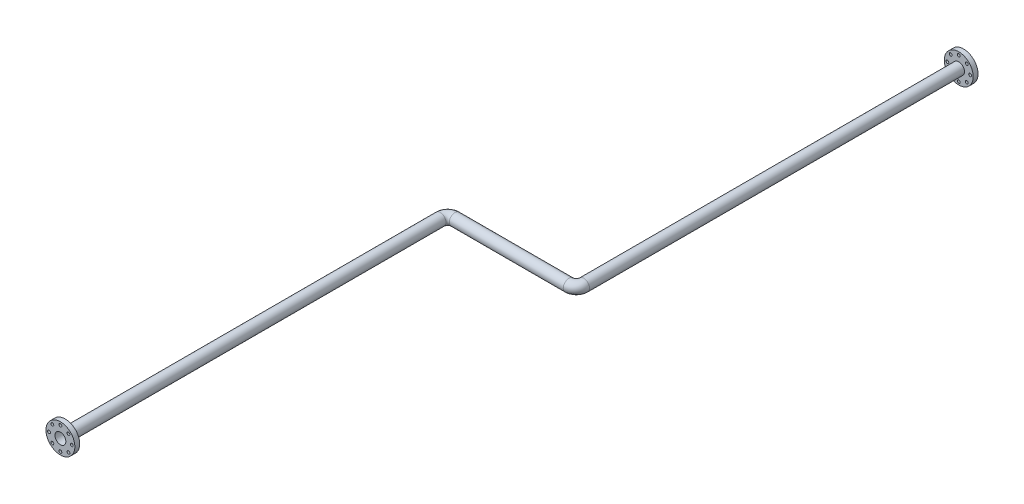
SolidWorks part; units mm, degrees
ref_plane "정면" through (0, 0, 0) normal (0, 0, 1) x (1, 0, 0)
ref_plane "윗면" through (0, 0, 0) normal (0, 1, 0) x (1, 0, 0)
ref_plane "우측면" through (0, 0, 0) normal (1, 0, 0) x (0, 0, -1)
sketch "스케치1" plane through (0, 0, 0) normal (1, 0, 0) x (0, 0, -1)
  circle A0 centre (0, 0) radius 30.25
  circle A1 centre (0, 0) radius 28.65
  dimension "D1" = 60.5
  dimension "D2" = 57.3
extrude "보스-돌출1" add sketch "스케치1" along normal mid plane 600
sketch "스케치2" plane through (300, 0, 0) normal (1, 0, 0) x (0, 0, -1)
  line L0 (39, 37.7289) -> (39, -37.7289) construction
  circle A0 centre (0, 0) radius 28.65
  circle A1 centre (0, 0) radius 30.25
  circle A2 centre (0, 0) radius 30.25 construction
  circle A3 centre (0, 0) radius 28.65 construction
  point P7 (39, 0)
  dimension "D1" = 39
revolve "회전1" add sketch "스케치2" angle 90 about L0
sketch "스케치3" plane through (-300, 0, 0) normal (-1, 0, 0) x (0, 0, 1)
  line L0 (39, 42.1657) -> (39, -42.1657) construction
  circle A0 centre (0, 0) radius 28.65
  circle A1 centre (0, 0) radius 30.25
  circle A2 centre (0, 0) radius 30.25 construction
  circle A3 centre (0, 0) radius 28.65 construction
  point P6 (39, 0)
  dimension "D1" = 39
revolve "회전2" add sketch "스케치3" angle 90 about L0
sketch "스케치4" plane through (0, 0, -39) normal (0, 0, -1) x (-1, 0, 0)
  circle A0 centre (-339, 0) radius 28.65
  circle A1 centre (-339, 0) radius 30.25
  circle A2 centre (-339, 0) radius 30.25 construction
  circle A3 centre (-339, 0) radius 28.65 construction
extrude "보스-돌출2" add sketch "스케치4" along normal blind 2000
sketch "스케치5" plane through (0, 0, 39) normal (0, 0, 1) x (1, 0, 0)
  circle A0 centre (-339, 0) radius 28.65
  circle A1 centre (-339, 0) radius 30.25
  circle A2 centre (-339, 0) radius 30.25 construction
  circle A3 centre (-339, 0) radius 28.65 construction
extrude "보스-돌출3" add sketch "스케치5" along normal blind 2000
sketch "스케치6" plane through (0, 0, 2039) normal (0, 0, 1) x (1, 0, 0)
  line L0 (-339, 60) -> (-339, 0) construction
  circle A0 centre (-339, 0) radius 76
  circle A1 centre (-339, 0) radius 28.65
  circle A2 centre (-339, 0) radius 28.65 construction
  circle A3 centre (-339, 60) radius 7.5
  circle A4 centre (-296.5736, 42.4264) radius 7.5
  circle A5 centre (-279, 0) radius 7.5
  circle A6 centre (-296.5736, -42.4264) radius 7.5
  circle A7 centre (-339, -60) radius 7.5
  circle A8 centre (-381.4264, -42.4264) radius 7.5
  circle A9 centre (-399, 0) radius 7.5
  circle A10 centre (-381.4264, 42.4264) radius 7.5
  point P24 (-339, 0)
  dimension "D1" = 152
  dimension "D2" = 15
  dimension "D3" = 60
  dimension "D4" = 8
extrude "보스-돌출4" add sketch "스케치6" against normal blind 25.5
sketch "스케치7" plane through (0, 0, -2039) normal (0, 0, -1) x (-1, 0, 0)
  line L0 (-339, 0) -> (-339, 60) construction
  circle A0 centre (-339, 0) radius 76
  circle A1 centre (-339, 0) radius 28.65
  circle A2 centre (-339, 0) radius 28.65 construction
  circle A3 centre (-339, 60) radius 7.5
  circle A4 centre (-296.5736, 42.4264) radius 7.5
  circle A5 centre (-279, 0) radius 7.5
  circle A6 centre (-296.5736, -42.4264) radius 7.5
  circle A7 centre (-339, -60) radius 7.5
  circle A8 centre (-381.4264, -42.4264) radius 7.5
  circle A9 centre (-399, 0) radius 7.5
  circle A10 centre (-381.4264, 42.4264) radius 7.5
  point P23 (-339, 0)
  dimension "D1" = 152
  dimension "D3" = 15
  dimension "D2" = 60
  dimension "D4" = 8
extrude "보스-돌출5" add sketch "스케치7" against normal blind 25.5
